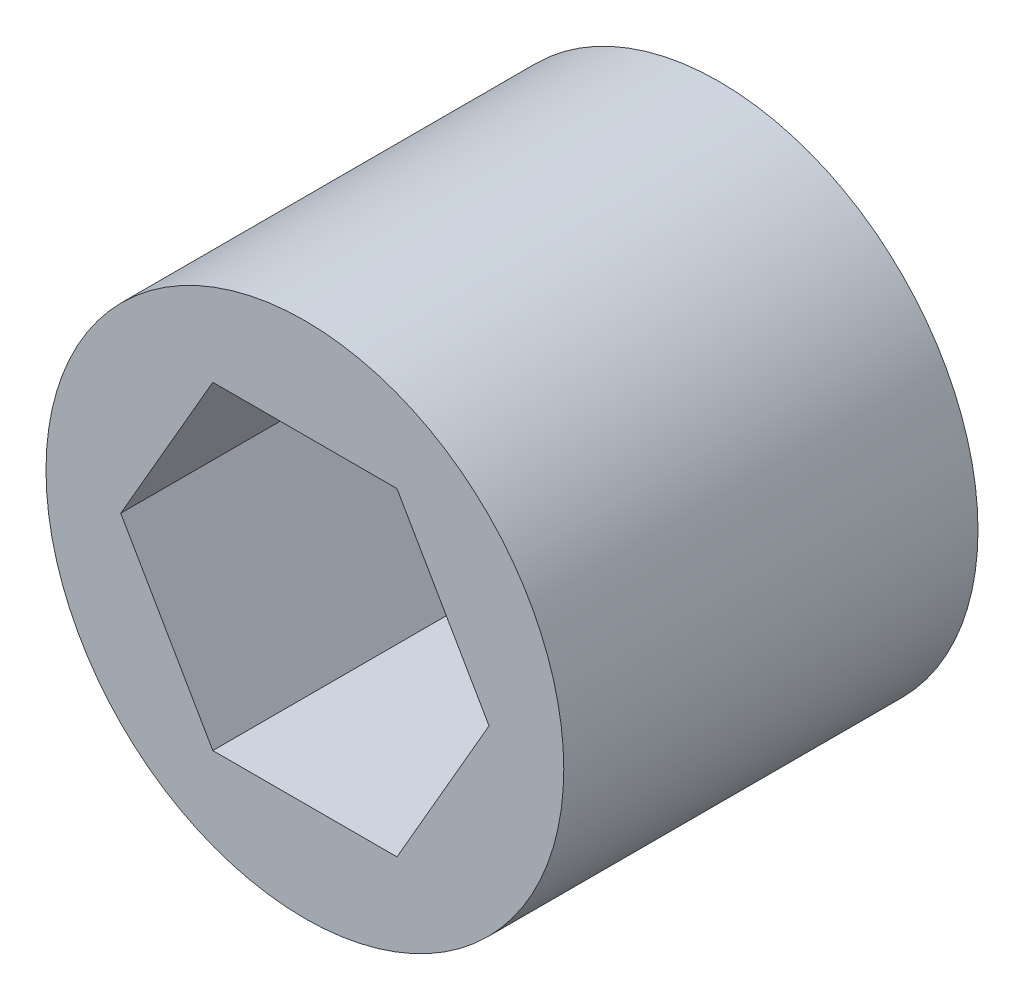
SolidWorks part; units mm, degrees
material "Delrin 2700 NC010, Low Viscosity Acetal Copolymer (SS)"
ref_plane "Front" through (0, 0, 0) normal (0, 0, 1) x (1, 0, 0)
ref_plane "Top" through (0, 0, 0) normal (0, 1, 0) x (1, 0, 0)
ref_plane "Right" through (0, 0, 0) normal (1, 0, 0) x (0, 0, -1)
sketch "Sketch2" plane through (0, 0, 0) normal (0, 0, 1) x (1, 0, 0)
  line L1 (-2.823, 4.8895) -> (-5.6459, 0)
  line L2 (-5.6459, 0) -> (-2.823, -4.8895)
  line L3 (-2.823, -4.8895) -> (2.823, -4.8895)
  line L4 (2.823, -4.8895) -> (5.6459, 0)
  line L5 (5.6459, 0) -> (2.823, 4.8895)
  line L6 (2.823, 4.8895) -> (-2.823, 4.8895)
  circle A0 centre (0, 0) radius 7.9375
  circle A1 centre (0, 0) radius 4.8895 construction
  dimension "D1" = 15.875
  dimension "D2" = 9.779
extrude "Boss-Extrude2" add sketch "Sketch2" along normal mid plane 12.7
